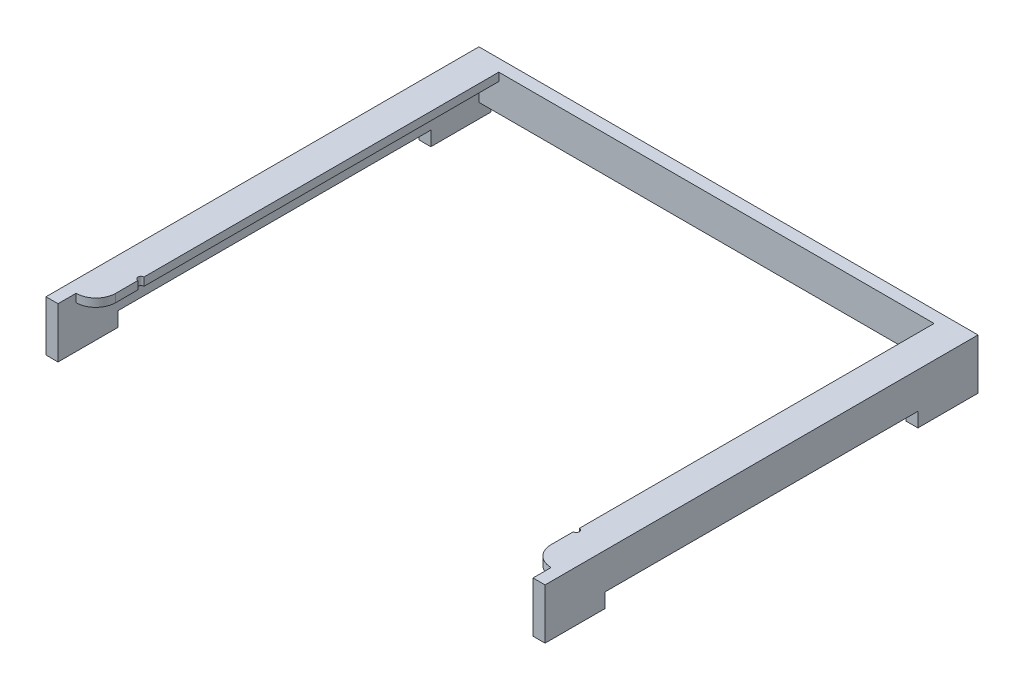
SolidWorks part; units mm, degrees
ref_plane "Front Plane" through (0, 0, 0) normal (0, 0, 1) x (1, 0, 0)
ref_plane "Top Plane" through (0, 0, 0) normal (0, 1, 0) x (1, 0, 0)
ref_plane "Right Plane" through (0, 0, 0) normal (1, 0, 0) x (0, 0, -1)
sketch "Sketch1" plane through (0, 0, 0) normal (0, 1, 0) x (1, 0, 0)
  line L0 (0, 0) -> (0, 72)
  line L1 (0, 72) -> (83, 72)
  line L2 (83, 72) -> (83, 0)
  line L3 (83, 0) -> (81, 0)
  line L4 (81, 0) -> (81, 70)
  line L5 (81, 70) -> (2, 70)
  line L6 (2, 70) -> (2, 0)
  line L7 (2, 0) -> (0, 0)
  line L8 (2, 70) -> (2, 72) construction
  dimension "D1" = 2
  dimension "D2" = 70
  dimension "D3" = 79
extrude "Boss-Extrude1" add sketch "Sketch1" along normal blind 6
ref_plane "Plane1" through (41.5, 0, 0) normal (1, 0, 0) x (0, 0, -1)
sketch "Sketch2" plane through (0, 6, 0) normal (0, 1, 0) x (1, 0, 0)
  line L0 (2, 70) -> (81, 70) construction
  line L1 (2, 3) -> (5.3, 3) construction
  line L2 (2, 3) -> (2, 70)
  line L3 (2, 70) -> (5.3, 70)
  line L4 (5.3, 3) -> (5.3, 70) construction
  line L5 (5.3, 6.3) -> (5.3, 10)
  line L10 (41.5, 70) -> (41.5, 0) construction
  line L11 (5.3, 11) -> (5.3, 70)
  line L12 (4.8, 10.5) -> (5.3, 10.5) construction
  arc A0 (5.3, 10) -> (5.3, 11) centre (5.3, 10.5) cw
  arc A1 (2, 3) -> (5.3, 6.3) centre (2, 6.3) ccw
  dimension "D3" = 0.5
  dimension "D1" = 36.2
  dimension "D2" = 67
  dimension "D4" = 7
extrude "Boss-Extrude2" add sketch "Sketch2" against normal blind 1.35
sketch "Sketch3" plane through (0, 0, 0) normal (0, -1, 0) x (1, 0, 0)
  line L0 (2, 0) -> (2, -70) construction
  line L1 (0, 0) -> (2, 0)
  line L2 (0, 0) -> (0, -10)
  line L3 (0, -10) -> (2, -10)
  line L4 (2, 0) -> (2, -10)
  line L6 (0, -72) -> (2, -72)
  line L7 (0, -72) -> (0, -62)
  line L8 (0, -62) -> (2, -62)
  line L9 (2, -72) -> (2, -62)
  dimension "D1" = 10
  dimension "D2" = 10
extrude "Boss-Extrude3" add sketch "Sketch3" along normal blind 2.4
mirror "Mirror1" about plane through (41.5, 0, 0) normal (1, 0, 0) of "Boss-Extrude3", "Boss-Extrude2"
